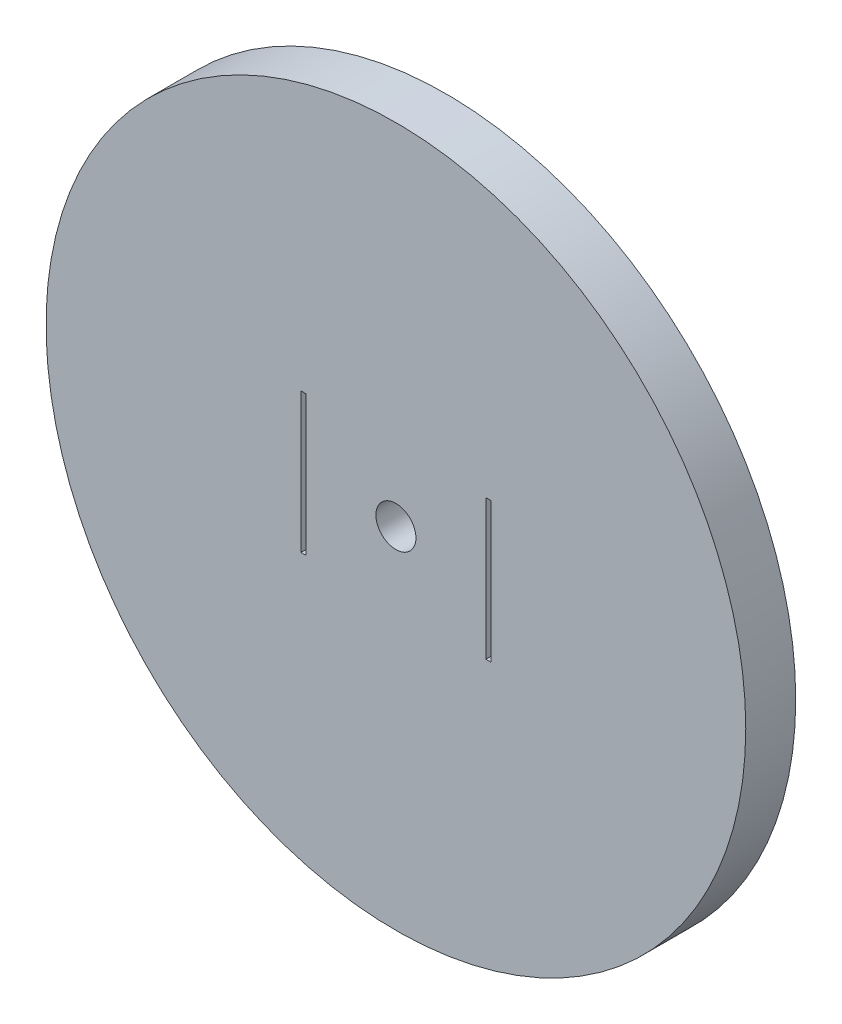
SolidWorks part; units mm, degrees
ref_plane "Front Plane" through (0, 0, 0) normal (0, 0, 1) x (1, 0, 0)
ref_plane "Top Plane" through (0, 0, 0) normal (0, 1, 0) x (1, 0, 0)
ref_plane "Right Plane" through (0, 0, 0) normal (1, 0, 0) x (0, 0, -1)
sketch "Sketch1" plane through (0, 0, 0) normal (0, 0, 1) x (1, 0, 0)
  line L0 (0, 10.3237) -> (0, -11.9962) construction
  line L1 (-9.5, 7) -> (-9, 7)
  line L2 (-9.5, 7) -> (-9.5, -7)
  line L3 (-9.5, -7) -> (-9, -7)
  line L4 (-9, 7) -> (-9, -7)
  line L5 (9, 7) -> (9, -7)
  line L6 (9.5, -7) -> (9, -7)
  line L7 (9.5, 7) -> (9.5, -7)
  line L8 (9.5, 7) -> (9, 7)
  circle A0 centre (0, 0) radius 35
  circle A1 centre (0, 0) radius 2
  dimension "D1" = 4
  dimension "D2" = 70
  dimension "D3" = 0.5
  dimension "D4" = 9
  dimension "D5" = 7
  dimension "D6" = 7
extrude "Boss-Extrude1" add sketch "Sketch1" along normal blind 5
sketch "Sketch3" plane through (0, 0, 0) normal (0, 1, 0) x (1, 0, 0)
  line L0 (-28, 14.6321) -> (-28, 0) construction
  line L1 (35, 0) -> (-35, 0) construction
  line L2 (-32.35, 14.6321) -> (-32.35, 0)
  line L3 (-32.35, 0) -> (-28, 0)
  line L4 (-28, 0) -> (-28, 18.9821)
  line L5 (-35, 0) -> (-35, -5) construction
  circle A0 centre (-28, 14.6321) radius 4.35 construction
  arc A1 (-32.35, 14.6321) -> (-28, 18.9821) centre (-28, 14.6321) cw
  dimension "D1" = 8.7
  dimension "D2" = 7
revolve "Revolve1" add sketch "Sketch3" angle 360 about L0
